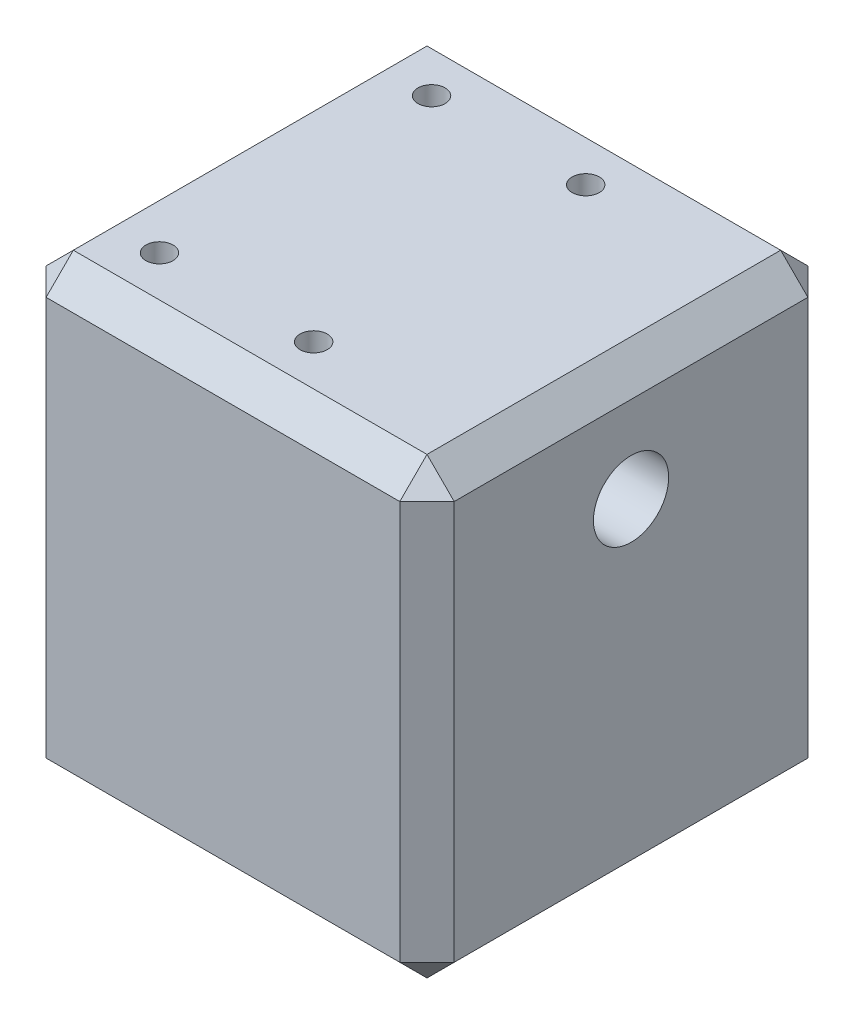
SolidWorks part; units mm, degrees
ref_plane "前视基准面" through (0, 0, 0) normal (0, 0, 1) x (1, 0, 0)
ref_plane "上视基准面" through (0, 0, 0) normal (0, 1, 0) x (1, 0, 0)
ref_plane "右视基准面" through (0, 0, 0) normal (1, 0, 0) x (0, 0, -1)
sketch "Sketch1" plane through (0, 0, 0) normal (0, 1, 0) x (1, 0, 0)
  line L1 (-22.5, 22.5) -> (22.5, 22.5)
  line L2 (-22.5, 22.5) -> (-22.5, -22.5)
  line L3 (-22.5, -22.5) -> (22.5, -22.5)
  line L4 (22.5, 22.5) -> (22.5, -22.5)
  line L5 (-22.5, 22.5) -> (22.5, -22.5) construction
  line L6 (-22.5, -22.5) -> (22.5, 22.5) construction
  point P0 (0, 0)
  dimension "D1" = 45
  dimension "D2" = 45
extrude "Boss-Extrude1" add sketch "Sketch1" along normal blind 50
sketch "Sketch2" plane through (0, 0, -22.5) normal (0, 0, -1) x (-1, 0, 0)
  circle A0 centre (0, 12.5) radius 4.15
  dimension "D1" = 8.3
  dimension "D2" = 12.5
extrude "Cut-Extrude1" cut sketch "Sketch2" against normal blind 30
sketch "Sketch3" plane through (22.5, 0, 0) normal (-1, 0, 0) x (0, 0, 1)
  line L1 (-22.5, 50) -> (22.5, 50) construction
  circle A0 centre (0, 37.5) radius 4.15
  dimension "D1" = 8.3
  dimension "D2" = 12.5
extrude "Cut-Extrude2" cut sketch "Sketch3" along normal blind 30
chamfer "Chamfer1" distance 3 angle 45 12 edges at (0, 0, -22.5) (22.5, 0, 0) (22.5, 25, 22.5) (0, 0, 22.5) (-22.5, 25, -22.5) (-22.5, 0, 0) (-22.5, 25, 22.5) (0, 50, 22.5) (-22.5, 50, 0) (0, 50, -22.5) (22.5, 50, 0) (22.5, 25, -22.5)
sketch "Sketch4" plane through (0, 50, 0) normal (0, 1, 0) x (1, 0, 0)
  line L0 (0, 0) -> (-7.6022, 0) construction
  circle A0 centre (-14.5, -15) radius 1.5
  circle A1 centre (2.5, -15) radius 1.5
  circle A2 centre (2.5, 15) radius 1.5
  circle A3 centre (-14.5, 15) radius 1.5
  point P9 (-14.5, -15)
  dimension "D1" = 3
  dimension "D2" = 3
extrude "Cut-Extrude3" cut sketch "Sketch4" against normal blind 10
